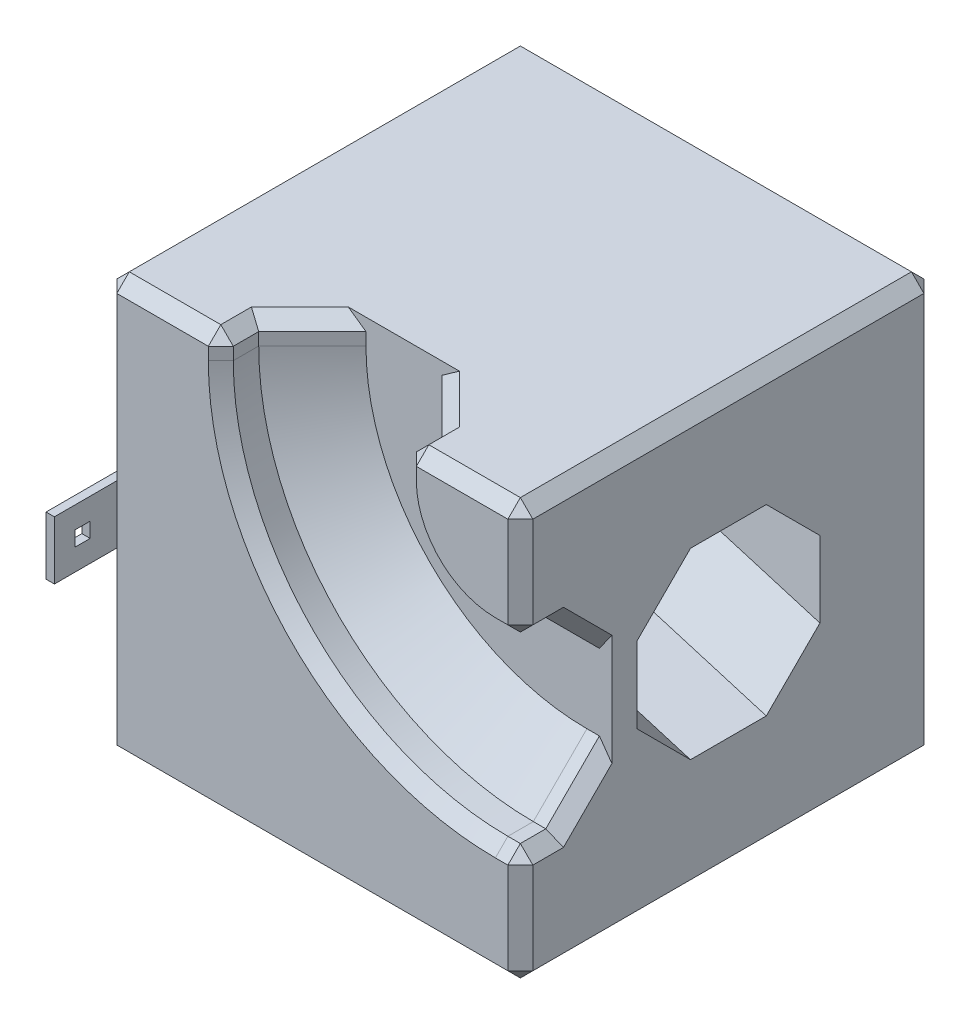
SolidWorks part; units mm, degrees
ref_plane "Front" through (0, 0, 0) normal (0, 0, 1) x (1, 0, 0)
ref_plane "Top" through (0, 0, 0) normal (0, 1, 0) x (1, 0, 0)
ref_plane "Right" through (0, 0, 0) normal (1, 0, 0) x (0, 0, -1)
sketch "Sketch1" plane through (0, 0, 0) normal (0, 0, 1) x (1, 0, 0)
  line L1 (0, 0) -> (50, 0)
  line L2 (0, 0) -> (0, 50)
  line L3 (0, 50) -> (50, 50)
  line L4 (50, 0) -> (50, 50)
  dimension "D1" = 50
extrude "Boss-Extrude1" add sketch "Sketch1" along normal blind 50
sketch "Sketch2" plane through (50, 0, 0) normal (-1, 0, 0) x (0, 0, 1)
  line L0 (25, 25) -> (25, 50) construction
  line L1 (50, 25) -> (25, 25) construction
  line L2 (50, 50) -> (50, 0) construction
  line L7 (50, 50) -> (0, 50) construction
  line L10 (14, 36) -> (36, 36) construction
  line L11 (14, 36) -> (14, 14) construction
  line L12 (14, 14) -> (36, 14) construction
  line L13 (36, 36) -> (36, 14) construction
  line L14 (36, 29.5563) -> (29.5563, 36)
  line L15 (14, 36) -> (36, 14) construction
  line L16 (29.5563, 36) -> (20.4437, 36)
  line L17 (14, 14) -> (36, 36) construction
  line L26 (20.4437, 36) -> (14, 29.5563)
  line L27 (14, 29.5563) -> (14, 20.4437)
  line L28 (14, 20.4437) -> (20.4437, 14)
  line L29 (20.4437, 14) -> (29.5563, 14)
  line L30 (29.5563, 14) -> (36, 20.4437)
  line L31 (36, 20.4437) -> (36, 29.5563)
  circle A1 centre (25, 25) radius 11 construction
  point P5 (25, 25)
  dimension "D1" = 22
sketch "Sketch3" plane through (0, 50, 0) normal (0, -1, 0) x (1, 0, 0)
  line L0 (0, 50) -> (50, 50) construction
  line L7 (14, 61) -> (36, 61) construction
  line L8 (14, 61) -> (14, 39) construction
  line L9 (14, 39) -> (36, 39) construction
  line L10 (36, 61) -> (36, 39) construction
  line L11 (14, 61) -> (36, 39) construction
  line L12 (14, 39) -> (36, 61) construction
  line L16 (29.5563, 39) -> (36, 45.4437)
  line L17 (36, 45.4437) -> (36, 54.5563)
  line L18 (36, 54.5563) -> (29.5563, 61)
  line L19 (29.5563, 61) -> (20.4437, 61)
  line L20 (20.4437, 61) -> (14, 54.5563)
  line L21 (14, 54.5563) -> (14, 45.4437)
  line L22 (14, 45.4437) -> (20.4437, 39)
  line L23 (20.4437, 39) -> (29.5563, 39)
  circle A0 centre (25, 50) radius 11 construction
  point P5 (25, 50)
  dimension "D1" = 22
sketch "Sketch4" plane through (0, 0, 50) normal (0, 0, 1) x (1, 0, 0)
  line L0 (25, 50) -> (25, 47)
  line L1 (47, 25) -> (50, 25)
  line L2 (50, 0) -> (50, 50) construction
  arc A0 (25, 47) -> (47, 25) centre (47, 47) ccw
  dimension "D1" = 22
sweep "Cut-Sweep2" cut profiles "Sketch3" path "Sketch4"
sketch "Sketch5" plane through (0, 0, 0) normal (-1, 0, 0) x (0, 0, 1)
  line L0 (36, 20.4437) -> (36, 29.5563) construction
  line L1 (24.5, 20.4437) -> (24.5, 29.5563)
  line L2 (24.5, 29.5563) -> (18.0563, 36)
  line L3 (18.0563, 36) -> (8.9437, 36)
  line L4 (8.9437, 36) -> (2.5, 29.5563)
  line L5 (2.5, 29.5563) -> (2.5, 20.4437)
  line L6 (2.5, 20.4437) -> (8.9437, 14)
  line L7 (8.9437, 14) -> (18.0563, 14)
  line L8 (18.0563, 14) -> (24.5, 20.4437)
  line L9 (20.4437, 14) -> (29.5563, 14) construction
  line L10 (0, 25) -> (25, 25) construction
  line L11 (0, 50) -> (0, 0) construction
  circle A0 centre (13.5, 25) radius 11 construction
  dimension "D1" = 2.5
loft "Cut-Loft1" cut profiles "Sketch5", "Sketch2"
chamfer "Chamfer1" distance 1.5 angle 45 28 edges at (48.5, 14, 50) (14, 48.5, 50) (23.6655, 23.6655, 50) (36, 48.5, 50) (39.2218, 39.2218, 50) (0, 25, 0) (25, 50, 0) (0, 50, 25) (32.7782, 50, 42.2218) (36, 50, 47.7218) (25, 0, 0) (0, 0, 25) (17.2218, 50, 42.2218) (14, 50, 47.7218) (7, 50, 50) (0, 25, 50) (25, 0, 50) (50, 17.2218, 42.2218) (50, 14, 47.7218) (50, 7, 50) (50, 0, 25) (50, 25, 0) (50, 50, 25) (50, 32.7782, 42.2218) (43, 50, 50) (50, 43, 50) (48.5, 36, 50) (50, 36, 47.7218)
sketch "Sketch6" plane through (0, 0, 50) normal (0, 0, 1) x (1, 0, 0)
  line L0 (0, 1.5) -> (0, 48.5) construction
  line L1 (0, 28.5) -> (1, 28.5)
  line L2 (0, 28.5) -> (0, 21.5)
  line L3 (0, 21.5) -> (1, 21.5)
  line L4 (1, 28.5) -> (1, 21.5)
  point P6 (0, 25)
  dimension "D1" = 1
  dimension "D2" = 7
extrude "Boss-Extrude2" add sketch "Sketch6" along normal blind 7 and the other way blind 7
sketch "Sketch7" plane through (1, 0, 0) normal (1, 0, 0) x (0, 0, -1)
  line L0 (-57, 21.5) -> (-57, 28.5) construction
  line L1 (-54.5, 24.1) -> (-52.7, 24.1)
  line L2 (-54.5, 24.1) -> (-54.5, 25.9)
  line L3 (-54.5, 25.9) -> (-52.7, 25.9)
  line L4 (-52.7, 24.1) -> (-52.7, 25.9)
  line L5 (-54.5, 25) -> (-57, 25) construction
  dimension "D1" = 2.5
  dimension "D2" = 1.8
extrude "Cut-Extrude1" cut sketch "Sketch7" against normal blind 7
